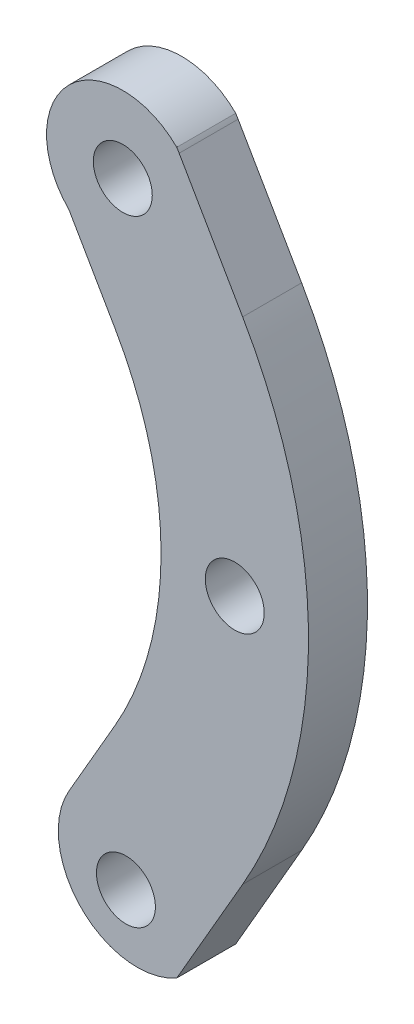
SolidWorks part; units mm, degrees
ref_plane "Front Plane" through (0, 0, 0) normal (0, 0, 1) x (1, 0, 0)
ref_plane "Top Plane" through (0, 0, 0) normal (0, 1, 0) x (1, 0, 0)
ref_plane "Right Plane" through (0, 0, 0) normal (1, 0, 0) x (0, 0, -1)
sketch "Sketch1" plane through (0, 0, 0) normal (0, 0, 1) x (1, 0, 0)
  line L0 (-82.5163, 0) -> (93.4038, 0) construction
  line L1 (0, 70.9124) -> (-2.5786, -79.7944) construction
  line L2 (-1.2133, 0) -> (31.7562, 32.9696) construction
  line L3 (-1.2133, 0) -> (30.212, -31.4253) construction
  line L4 (-1.2133, 0) -> (72.3988, 42.5) construction
  line L5 (-1.2133, 0) -> (40.9629, -24.3504) construction
  line L6 (29.0976, 17.5) -> (24.4084, 25.6218)
  line L7 (29.0976, -17.5) -> (24.4084, -25.6218)
  line L8 (42.0879, 25) -> (35.6271, 36.1905)
  line L9 (72.3988, 42.5) -> (52.8856, 31.234) construction
  line L10 (31.7562, 32.9696) -> (51.3153, 52.5286) construction
  line L11 (35.6271, 36.1905) -> (35.3897, 36.603)
  line L12 (30.212, -31.4253) -> (52.8856, -54.0989) construction
  line L13 (40.9629, -24.3504) -> (57.8482, -34.0992) construction
  line L14 (42.0879, -25) -> (35.3892, -36.6025)
  arc A0 (29.0976, 17.5) -> (29.0976, -17.5) centre (-1.2133, 0) cw
  arc A1 (42.0879, 25) -> (42.0879, -25) centre (-1.2133, 0) cw
  arc A2 (24.4084, -25.6218) -> (35.3892, -36.6025) centre (31.37, -29.641) ccw
  arc A4 (35.6271, 36.1905) -> (35.3789, 36.5922) centre (28.7695, 32.2312) ccw
  arc A5 (24.4084, 25.6218) -> (35.3789, 36.5922) centre (29.8937, 31.107) cw
  circle A6 centre (41.2867, 0) radius 3
  circle A8 centre (30.212, -31.4253) radius 3
  circle A9 centre (29.8937, 31.107) radius 3
  dimension "D1" = 30
  dimension "D2" = 45
  dimension "D3" = 45
  dimension "D4" = 30
extrude "Boss-Extrude1" add sketch "Sketch1" along normal blind 6
